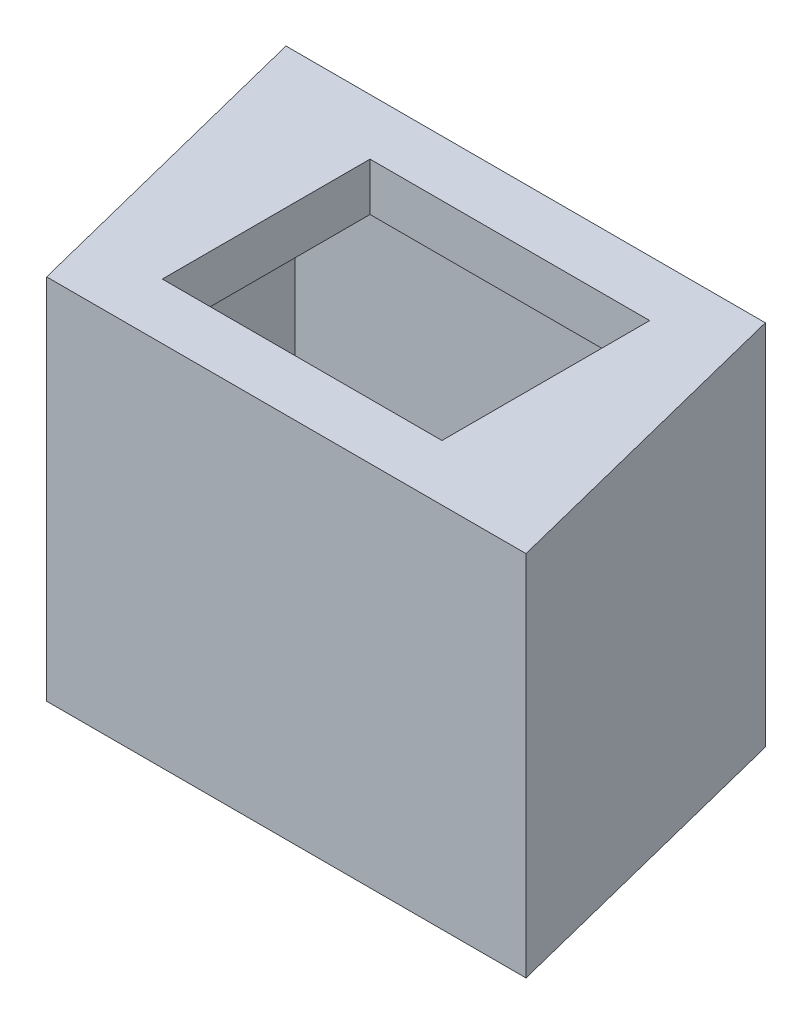
SolidWorks part; units mm, degrees
ref_plane "Спереди" through (0, 0, 0) normal (0, 0, 1) x (1, 0, 0)
ref_plane "Сверху" through (0, 0, 0) normal (0, 1, 0) x (1, 0, 0)
ref_plane "Справа" through (0, 0, 0) normal (1, 0, 0) x (0, 0, -1)
sketch "Эскиз1" plane through (0, 0, 0) normal (0, 1, 0) x (1, 0, 0)
  line L0 (0, 0) -> (30, 0)
  line L1 (30, 0) -> (35.0237, -20)
  line L2 (35.0237, -20) -> (5.0237, -20)
  line L3 (5.0237, -20) -> (0, 0)
  dimension "D1" = 30
  dimension "D2" = 30
  dimension "D3" = 75.9
  dimension "D4" = 20
extrude "Бобышка-Вытянуть1" add sketch "Эскиз1" along normal blind 3
sketch "Эскиз2" plane through (0, 3, 0) normal (0, 1, 0) x (1, 0, 0)
  line L0 (2.5118, -10) -> (32.5118, -10) construction
  line L1 (0, 0) -> (5.0237, -20) construction
  line L2 (35.0237, -20) -> (30, 0) construction
  line L3 (17.5118, -10) -> (17.5118, 0) construction
  line L4 (8.7618, -3.5) -> (26.2618, -3.5)
  line L5 (8.7618, -3.5) -> (8.7618, -16.5)
  line L6 (8.7618, -16.5) -> (26.2618, -16.5)
  line L7 (26.2618, -3.5) -> (26.2618, -16.5)
  line L8 (30, 0) -> (0, 0) construction
  dimension "D1" = 17.5
  dimension "D2" = 13
  dimension "D3" = 6.5
  dimension "D4" = 8.75
extrude "Вырез-Вытянуть1" cut sketch "Эскиз2" against normal through all
sketch "Эскиз3" plane through (0, 0, 0) normal (0, -1, 0) x (1, 0, 0)
  line L0 (5.0237, 20) -> (0, 0)
  line L1 (0, 0) -> (30, 0)
  line L2 (30, 0) -> (35.0237, 20)
  line L3 (5.0237, 20) -> (35.0237, 20) construction
  line L4 (35.0237, 20) -> (30, 0) construction
  line L5 (35.0237, 20) -> (5.0237, 20)
  line L6 (6.5834, 18) -> (2.5645, 2)
  line L7 (2.5645, 2) -> (28.4402, 2)
  line L8 (28.4402, 2) -> (32.4592, 18)
  line L9 (32.4592, 18) -> (6.5834, 18)
  dimension "D1" = 2
  dimension "D2" = 2
  dimension "D3" = 2
  dimension "D4" = 2
extrude "Бобышка-Вытянуть2" add sketch "Эскиз3" along normal blind 20
